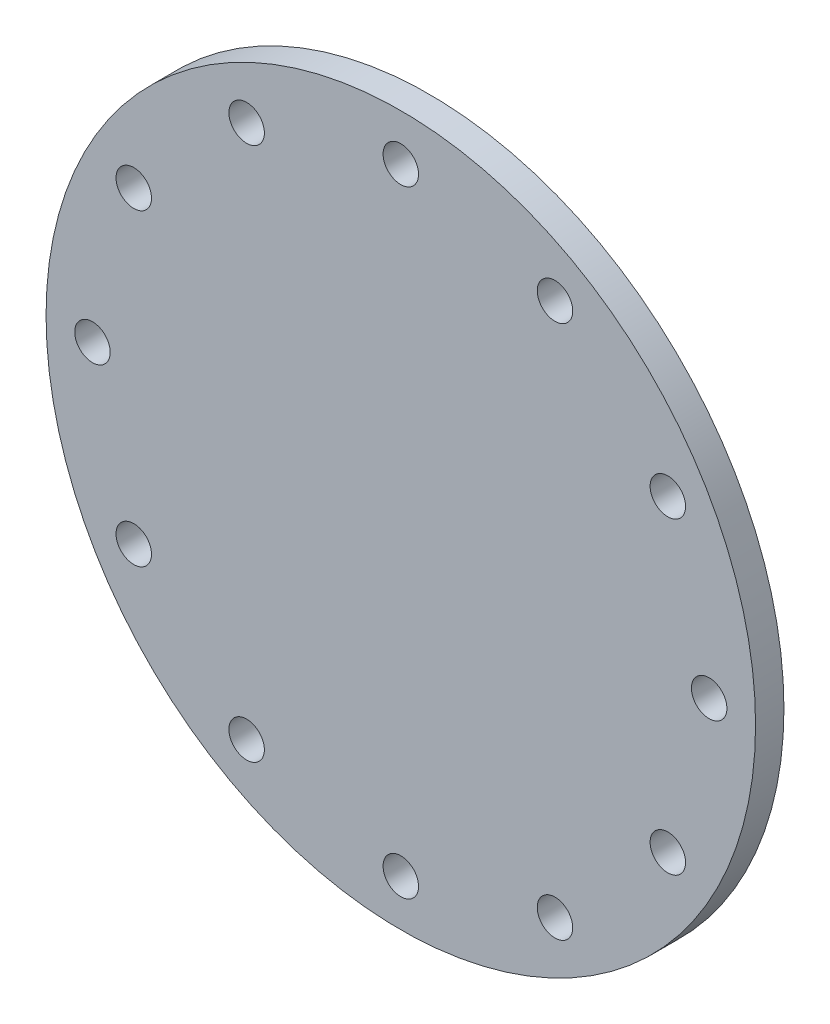
SolidWorks part; units mm, degrees
ref_plane "Front Plane" through (0, 0, 0) normal (0, 0, 1) x (1, 0, 0)
ref_plane "Top Plane" through (0, 0, 0) normal (0, 1, 0) x (1, 0, 0)
ref_plane "Right Plane" through (0, 0, 0) normal (1, 0, 0) x (0, 0, -1)
sketch "Sketch2" plane through (0, 0, 0) normal (0, 0, 1) x (1, 0, 0)
  circle A0 centre (0, 0) radius 250
  circle A1 centre (0, 217.2914) radius 12.5
  circle A2 centre (108.6457, 188.1799) radius 12.5
  circle A3 centre (188.1799, 108.6457) radius 12.5
  circle A4 centre (217.2914, 0) radius 12.5
  circle A5 centre (188.1799, -108.6457) radius 12.5
  circle A6 centre (108.6457, -188.1799) radius 12.5
  circle A7 centre (0, -217.2914) radius 12.5
  circle A8 centre (-108.6457, -188.1799) radius 12.5
  circle A9 centre (-188.1799, -108.6457) radius 12.5
  circle A10 centre (-217.2914, 0) radius 12.5
  circle A11 centre (-188.1799, 108.6457) radius 12.5
  circle A12 centre (-108.6457, 188.1799) radius 12.5
  point P30 (0, 0)
  dimension "D1" = 12
extrude "Boss-Extrude1" add sketch "Sketch2" along normal blind 20
